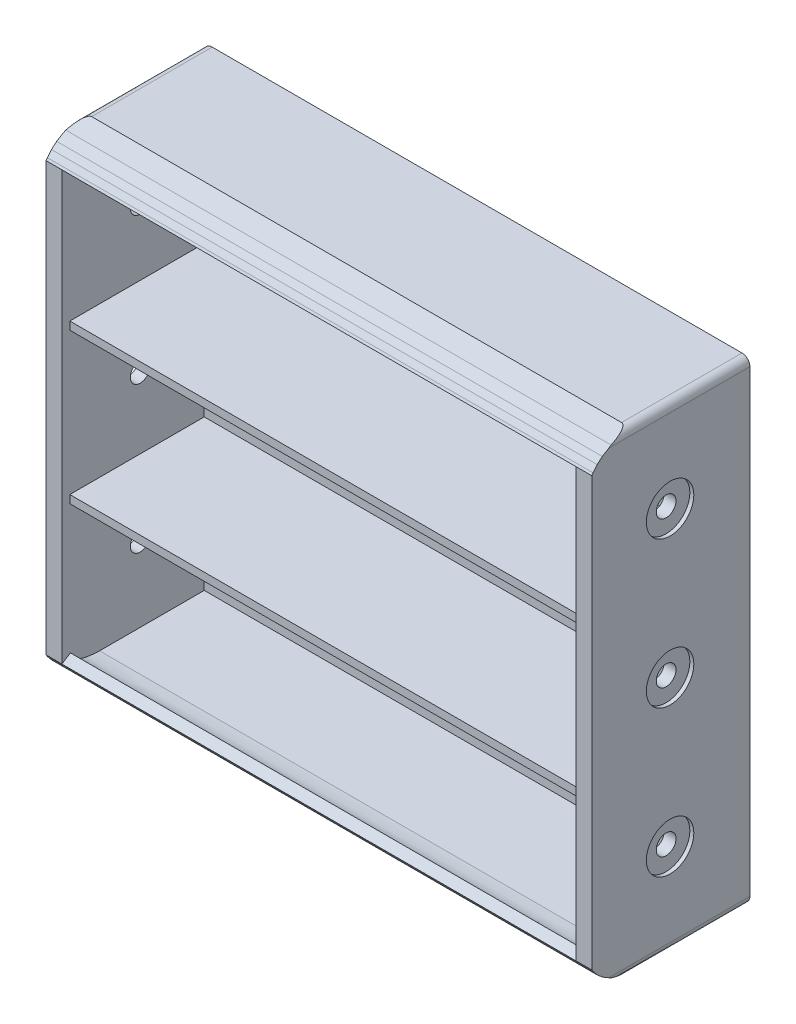
SolidWorks part; units mm, degrees
ref_plane "Front Plane" through (0, 0, 0) normal (0, 0, 1) x (1, 0, 0)
ref_plane "Top Plane" through (0, 0, 0) normal (0, 1, 0) x (1, 0, 0)
ref_plane "Right Plane" through (0, 0, 0) normal (1, 0, 0) x (0, 0, -1)
sketch "Sketch2" plane through (0, 0, 0) normal (0, 0, 1) x (1, 0, 0)
  line L1 (-34.5, -30) -> (34.5, -30)
  line L2 (-34.5, -30) -> (-34.5, 30)
  line L3 (-34.5, 30) -> (34.5, 30)
  line L4 (34.5, -30) -> (34.5, 30)
  line L5 (-34.5, -30) -> (34.5, 30) construction
  line L6 (-34.5, 30) -> (34.5, -30) construction
  line L7 (-32.5, -28) -> (32.5, -28)
  line L8 (-32.5, -28) -> (-32.5, 28)
  line L9 (-32.5, 28) -> (32.5, 28)
  line L10 (32.5, -28) -> (32.5, 28)
  line L11 (-32.5, -28) -> (32.5, 28) construction
  line L12 (-32.5, 28) -> (32.5, -28) construction
  point P0 (0, 0)
  point P6 (0, 0)
  dimension "D1" = 60
  dimension "D2" = 69
  dimension "D3" = 56
  dimension "D4" = 65
extrude "Boss-Extrude1" add sketch "Sketch2" along normal blind 19
sketch "Sketch3" plane through (0, 0, 0) normal (0, 0, -1) x (-1, 0, 0)
  line L1 (-34.5, -30) -> (34.5, -30)
  line L2 (-34.5, -30) -> (-34.5, 30)
  line L3 (-34.5, 30) -> (34.5, 30)
  line L4 (34.5, -30) -> (34.5, 30)
  line L5 (-34.5, -30) -> (34.5, 30) construction
  line L6 (-34.5, 30) -> (34.5, -30) construction
  point P0 (0, 0)
extrude "Boss-Extrude2" add sketch "Sketch3" against normal mid plane 2
sketch "Sketch4" plane through (-34.5, 0, 0) normal (-1, 0, 0) x (0, 0, 1)
  line L0 (9, -30) -> (14.2318, -30) construction
  line L1 (19, -30) -> (-1, -30) construction
  line L2 (19, 30) -> (19, -30) construction
  line L3 (19, -27.0621) -> (17.9177, -26.3858)
  line L4 (14.2318, -30) -> (13.3515, -28.0863)
  line L5 (0, 0) -> (24.9717, 0) construction
  line L6 (14.2318, 30) -> (13.3515, 28.0863)
  line L7 (19, 27.0621) -> (17.9177, 26.3858)
  spline S0 degree 2 poles (14.2318, -30) (17.7885, -29.1042) (19, -27.0621) knots 0 0 0 0.719469 0.719469 0.719469
  spline S1 degree 3 poles (17.9177, -26.3858) (17.0681, -28.2292) (14.9404, -27.8412) (13.3515, -28.0863) knots 0 0 0 0 1 1 1 1
  spline S2 degree 3 poles (17.9177, 26.3858) (17.0681, 28.2292) (14.9404, 27.8412) (13.3515, 28.0863) knots 0 0 0 0 1 1 1 1
  spline S3 degree 2 poles (14.2318, 30) (17.7885, 29.1042) (19, 27.0621) knots 0 0 0 0.719469 0.719469 0.719469
extrude "Boss-Extrude4" add sketch "Sketch4" along normal mid plane 135
sketch "Sketch6" plane through (-34.5, 0, 0) normal (-1, 0, 0) x (0, 0, 1)
  line L0 (19, -30) -> (19, -27.0621)
  line L1 (19, -30) -> (14.2318, -30)
  line L2 (0, 0) -> (34.2149, 0) construction
  line L3 (19, 30) -> (14.2318, 30)
  line L4 (19, 30) -> (19, 27.0621)
  parabola Q0 (14.2318, -30) -> (19, -27.0621) focus (17.2376, -25.8136) apex (19.1654, -26.7558) construction
  parabola Q1 (14.2318, -30) -> (19, -27.0621) focus (17.2376, -25.8136) apex (19.1654, -26.7558) construction
  parabola Q2 (14.2318, -30) -> (19, -27.0621) focus (17.2376, -25.8136) apex (19.1654, -26.7558) construction
  parabola Q3 (14.2318, -30) -> (19, -27.0621) focus (17.2376, -25.8136) apex (19.1654, -26.7558) construction
  spline S0 degree 1 poles (14.2318, -30) (16.5345, -29.1842) knots 0 0 1 1
  spline S1 degree 1 poles (16.5345, -29.1842) (17.6624, -28.5073) knots 0 0 1 1
  spline S2 degree 1 poles (17.6624, -28.5073) (18.3184, -27.941) knots 0 0 1 1
  spline S3 degree 1 poles (18.3184, -27.941) (18.8405, -27.3113) knots 0 0 1 1
  spline S4 degree 1 poles (18.8405, -27.3113) (19, -27.0621) knots 0 0 1 1
  spline S5 degree 1 poles (18.8405, 27.3113) (19, 27.0621) knots 0 0 1 1
  spline S6 degree 1 poles (18.3184, 27.941) (18.8405, 27.3113) knots 0 0 1 1
  spline S7 degree 1 poles (17.6624, 28.5073) (18.3184, 27.941) knots 0 0 1 1
  spline S8 degree 1 poles (16.5345, 29.1842) (17.6624, 28.5073) knots 0 0 1 1
  spline S9 degree 1 poles (14.2318, 30) (16.5345, 29.1842) knots 0 0 1 1
extrude "Cut-Extrude1" cut sketch "Sketch6" against normal blind 135
sketch "Sketch7" plane through (0, -30, 0) normal (0, -1, 0) x (1, 0, 0)
  line L0 (-34.5, -1) -> (-34.5, 25.8744)
  line L1 (-34.5, 25.8744) -> (-118.904, 25.8744)
  line L2 (-118.904, 25.8744) -> (-118.904, -1)
  line L3 (-118.904, -1) -> (-34.5, -1)
extrude "Cut-Extrude2" cut sketch "Sketch7" against normal blind 135
sketch "Sketch9" plane through (0, 0, 1) normal (0, 0, 1) x (1, 0, 0)
  line L0 (0, 0) -> (0, 9.5) construction
  line L1 (0, 0) -> (0, -9.5) construction
  line L2 (32.5, -28) -> (32.5, 28) construction
  line L3 (-32.5, 10) -> (32.5, 10)
  line L4 (-32.5, 10) -> (-32.5, 9)
  line L5 (-32.5, 9) -> (32.5, 9)
  line L6 (32.5, 10) -> (32.5, 9)
  line L7 (-32.5, 10) -> (32.5, 9) construction
  line L8 (-32.5, 9) -> (32.5, 10) construction
  line L9 (0, 0) -> (19.6514, 0) construction
  line L10 (-32.5, -9) -> (32.5, -10) construction
  line L11 (-32.5, -10) -> (32.5, -9) construction
  line L12 (32.5, -10) -> (32.5, -9)
  line L13 (-32.5, -9) -> (32.5, -9)
  line L14 (-32.5, -10) -> (-32.5, -9)
  line L15 (-32.5, -10) -> (32.5, -10)
  dimension "D1" = 9.5
  dimension "D2" = 1
extrude "Boss-Extrude5" add sketch "Sketch9" along normal blind 17
fillet "Fillet1" radius 1 4 edges at (-34.5, 30, 6.6159) (-34.5, -30, 6.6159) (34.5, 30, 6.6159) (34.5, -30, 6.6159)
sketch "Sketch10" plane through (34.5, 0, 0) normal (1, 0, 0) x (0, 0, -1)
  line L0 (0, 0) -> (-34.404, 0) construction
  line L1 (-9.0966, 0) -> (-9.0966, -29) construction
  line L2 (-16.8414, -29) -> (1, -29) construction
  circle A0 centre (-9.0966, -18.5) radius 3
  circle A1 centre (-9.0966, 0) radius 3
  circle A2 centre (-9.0966, 18.5) radius 3
  dimension "D2" = 6
  dimension "D1" = 18.5
  dimension "D3" = 3
extrude "Cut-Extrude6" cut sketch "Sketch10" against normal blind 0.5
sketch "Sketch11" plane through (34.5, 0, 0) normal (1, 0, 0) x (0, 0, -1)
  circle A0 centre (-9.0966, -18.5) radius 1.25
  circle A1 centre (-9.0966, 0) radius 1.25
  circle A2 centre (-9.0966, 18.5) radius 1.25
  dimension "D1" = 2.5
  dimension "D2" = 3
extrude "Cut-Extrude7" cut sketch "Sketch11" against normal up to surface (69 mm away) up to face at (-34.5, 0.1407, 14.9438)
mirror "Mirror1" about plane through (0, 0, 0) normal (1, 0, 0) of "Cut-Extrude6"
sketch "Sketch12" plane through (32.5, 0, 0) normal (-1, 0, 0) x (0, 0, 1)
  circle A0 centre (9.0966, 18.5) radius 3.5
  dimension "D1" = 7
